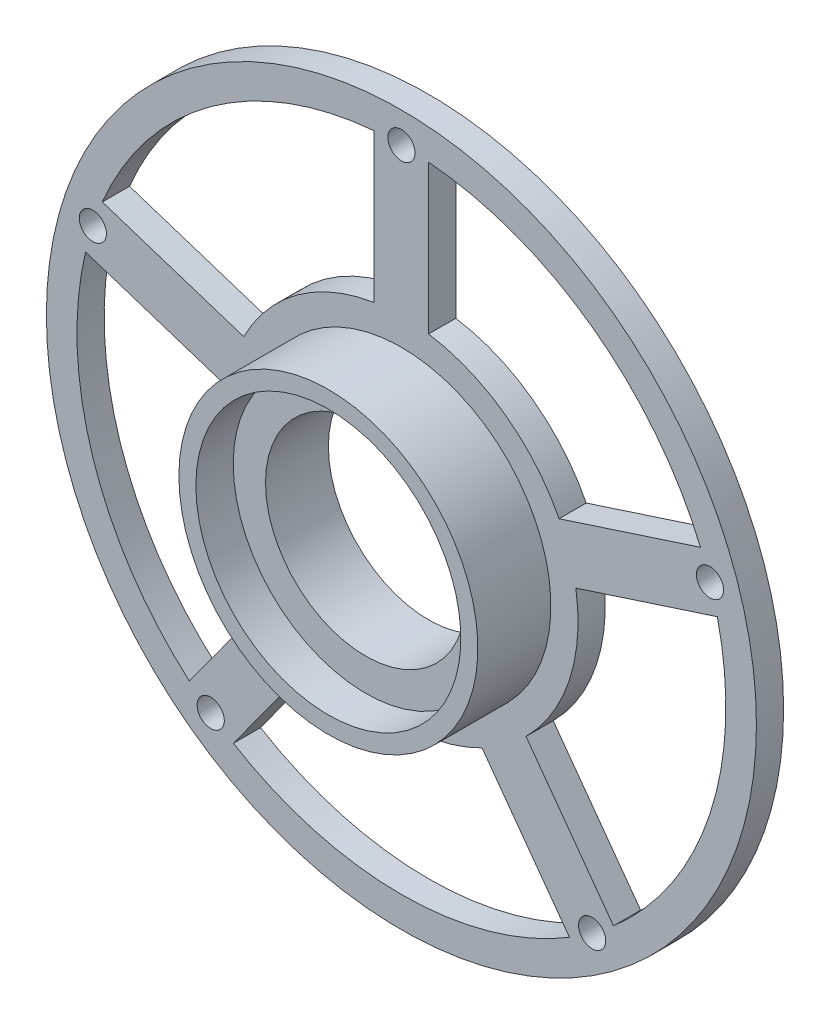
SolidWorks part; units mm, degrees
material "Nickel"
ref_plane "Front Plane" through (0, 0, 0) normal (0, 0, 1) x (1, 0, 0)
ref_plane "Top Plane" through (0, 0, 0) normal (0, 1, 0) x (1, 0, 0)
ref_plane "Right Plane" through (0, 0, 0) normal (1, 0, 0) x (0, 0, -1)
sketch "Sketch1" plane through (0, 0, 0) normal (1, 0, 0) x (0, 0, -1)
  line L0 (0, 0) -> (-24.5639, 0) construction
  line L1 (0, 14.986) -> (-9.398, 14.986)
  line L2 (-9.398, 14.986) -> (-9.398, 19.812)
  line L3 (-9.398, 19.812) -> (-14.986, 19.812)
  line L4 (-14.986, 19.812) -> (-14.986, 22.352)
  line L5 (-14.986, 22.352) -> (-4.064, 22.352)
  line L6 (-4.064, 22.352) -> (-4.064, 53.086)
  line L7 (-4.064, 53.086) -> (0, 53.086)
  line L8 (0, 53.086) -> (0, 14.986)
  point P8 (0, 0)
  dimension "D1" = 14.986
  dimension "D2" = 4.826
  dimension "D3" = 2.54
  dimension "D4" = 38.1
  dimension "D5" = 9.398
  dimension "D6" = 10.922
  dimension "D7" = 4.064
revolve "Revolve1" add sketch "Sketch1" angle 360 about L0
sketch "Sketch2" plane through (0, 0, 4.064) normal (0, 0, 1) x (1, 0, 0)
  line L0 (0, 56.4448) -> (0, 0) construction
  line L1 (0, 0) -> (64.1332, 20.8381) construction
  line L2 (4.064, 48.3435) -> (4.064, 26.1015)
  line L3 (23.5682, 11.9309) -> (44.7215, 18.8041)
  line L4 (4.064, 56.4448) -> (4.064, 5.5936) construction
  line L5 (4.064, 5.5936) -> (62.8774, 24.7032) construction
  arc A0 (23.5682, 11.9309) -> (4.064, 26.1015) centre (0, 0) ccw
  arc A1 (44.7215, 18.8041) -> (4.064, 48.3435) centre (0, 0) ccw
  circle A3 centre (0, 0) radius 22.352 construction
  circle A4 centre (0, 48.514) radius 2.032
  dimension "D1" = 22.098
  dimension "D2" = 4.064
  dimension "D5" = 4.064
  dimension "D3" = 72
  dimension "D4" = 4.064
extrude "Cut-Extrude1" cut sketch "Sketch2" against normal through all
pattern_circular "CirPattern1" count 5 over 360 about axis through (0, 0, 0) along (0, 0, 1) of "Cut-Extrude1"
